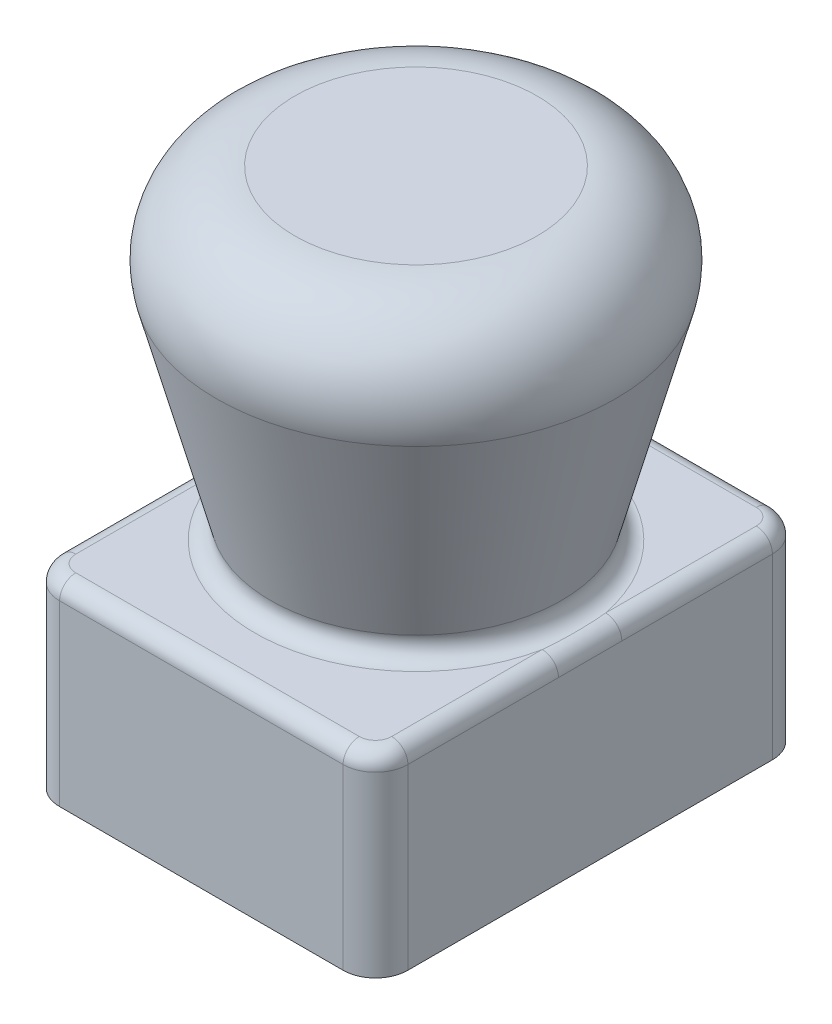
SolidWorks part; units mm, degrees
ref_plane "Plan de face" through (0, 0, 0) normal (0, 0, 1) x (1, 0, 0)
ref_plane "Plan de dessus" through (0, 0, 0) normal (0, 1, 0) x (1, 0, 0)
ref_plane "Plan de droite" through (0, 0, 0) normal (1, 0, 0) x (0, 0, -1)
sketch "Esquisse2" plane through (0, 0, 0) normal (0, 0, 1) x (1, 0, 0)
  line L0 (0, 0) -> (0, 20) construction
  line L1 (0, 20) -> (14, 20)
  line L2 (14, 20) -> (8.641, 0)
  line L3 (8.641, 0) -> (0, 0)
  line L4 (0, 0) -> (0, 20)
  point P3 (4.5807, 0)
  dimension "D1" = 105
  dimension "D2" = 28
  dimension "D3" = 20
revolve "Révolution1" add sketch "Esquisse2" angle 360 about L0
sketch "Esquisse3" plane through (0, 0, 0) normal (0, -1, 0) x (1, 0, 0)
  line L1 (-10.75, 13.25) -> (10.75, 13.25)
  line L2 (-10.75, 13.25) -> (-10.75, -13.25)
  line L3 (-10.75, -13.25) -> (10.75, -13.25)
  line L4 (10.75, 13.25) -> (10.75, -13.25)
  line L5 (-10.75, 13.25) -> (10.75, -13.25) construction
  line L6 (-10.75, -13.25) -> (10.75, 13.25) construction
  point P0 (0, 0)
  dimension "D1" = 26.5
  dimension "D2" = 21.5
extrude "Boss.-Extru.2" add sketch "Esquisse3" along normal blind 12
fillet "Congé1" radius 5 1 edges at (0, 20, -14)
fillet "Congé2" radius 2 4 edges at (-10.75, -6, 13.25) (10.75, -6, 13.25) (-10.75, -6, -13.25) (10.75, -6, -13.25)
fillet "Congé3" radius 1 1 edges at (0, 0, -8.641)
fillet "Congé4" radius 1 8 edges at (10.75, 0, 0) (10.1642, 0, -12.6642) (0, 0, -13.25) (-10.1642, 0, -12.6642) (-10.75, 0, 0) (10.1642, 0, 12.6642) (0, 0, 13.25) (-10.1642, 0, 12.6642)
sketch "Esquisse4" plane through (0, -12, 0) normal (0, -1, 0) x (1, 0, 0)
  circle A0 centre (0, 0) radius 6.1
  dimension "D1" = 12.2
extrude "Enlèv. mat.-Extru.1" cut sketch "Esquisse4" against normal blind 28
fillet "Congé5" radius 6 1 edges at (0, 16, -6.1)
